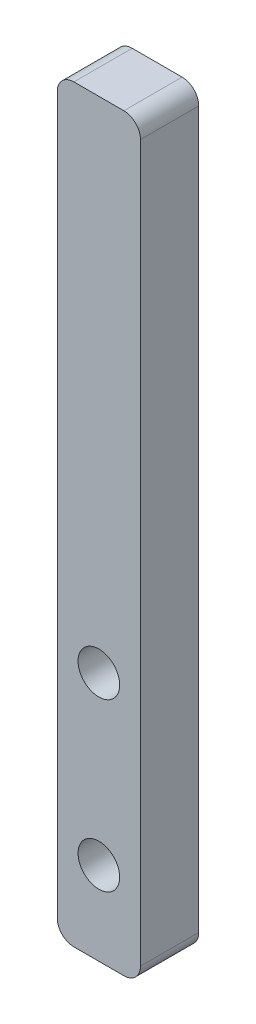
SolidWorks part; units mm, degrees
ref_plane "Alzado" through (0, 0, 0) normal (0, 0, 1) x (1, 0, 0)
ref_plane "Planta" through (0, 0, 0) normal (0, 1, 0) x (1, 0, 0)
ref_plane "Vista lateral" through (0, 0, 0) normal (1, 0, 0) x (0, 0, -1)
sketch "Croquis1" plane through (0, 0, 0) normal (0, 0, 1) x (1, 0, 0)
  line L1 (5, 45) -> (-5, 45)
  line L2 (5, 45) -> (5, -45)
  line L3 (5, -45) -> (-5, -45)
  line L4 (-5, 45) -> (-5, -45)
  line L5 (5, 45) -> (-5, -45) construction
  line L6 (5, -45) -> (-5, 45) construction
  point P0 (0, 0)
  dimension "D1" = 10
  dimension "D2" = 90
extrude "Saliente-Extruir1" add sketch "Croquis1" along normal blind 7
sketch "Croquis2" plane through (0, 0, 7) normal (0, 0, 1) x (1, 0, 0)
  line L0 (0, -45) -> (0, -35) construction
  line L1 (-5, -45) -> (5, -45) construction
  line L2 (0, -35) -> (0, -15) construction
  circle A0 centre (0, -35) radius 2.5
  circle A1 centre (0, -15) radius 2.5
  dimension "D1" = 20
extrude "Cortar-Extruir1" cut sketch "Croquis2" against normal through all
fillet "Redondeo1" radius 2 4 edges at (-5, -45, 3.5) (5, -45, 3.5) (-5, 45, 3.5) (5, 45, 3.5)
